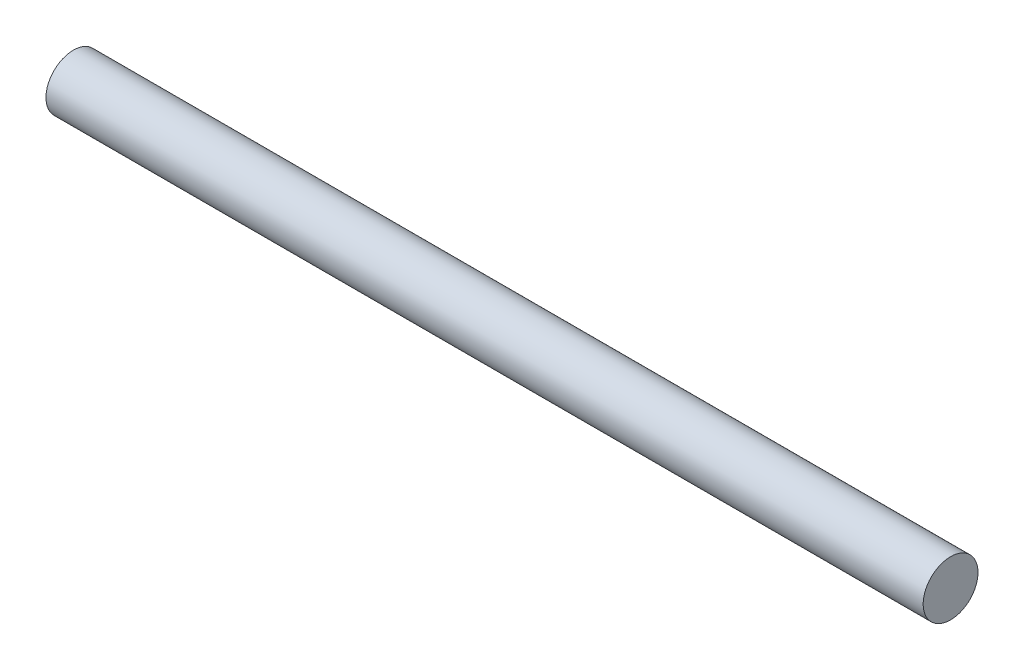
SolidWorks part; units mm, degrees
ref_plane "Front Plane" through (0, 0, 0) normal (0, 0, 1) x (1, 0, 0)
ref_plane "Top Plane" through (0, 0, 0) normal (0, 1, 0) x (1, 0, 0)
ref_plane "Right Plane" through (0, 0, 0) normal (1, 0, 0) x (0, 0, -1)
sketch "Sketch1" plane through (0, 0, 0) normal (1, 0, 0) x (0, 0, -1)
  circle A0 centre (0, 0) radius 3.175
extrude "Boss-Extrude1" add sketch "Sketch1" along normal mid plane 101.6
